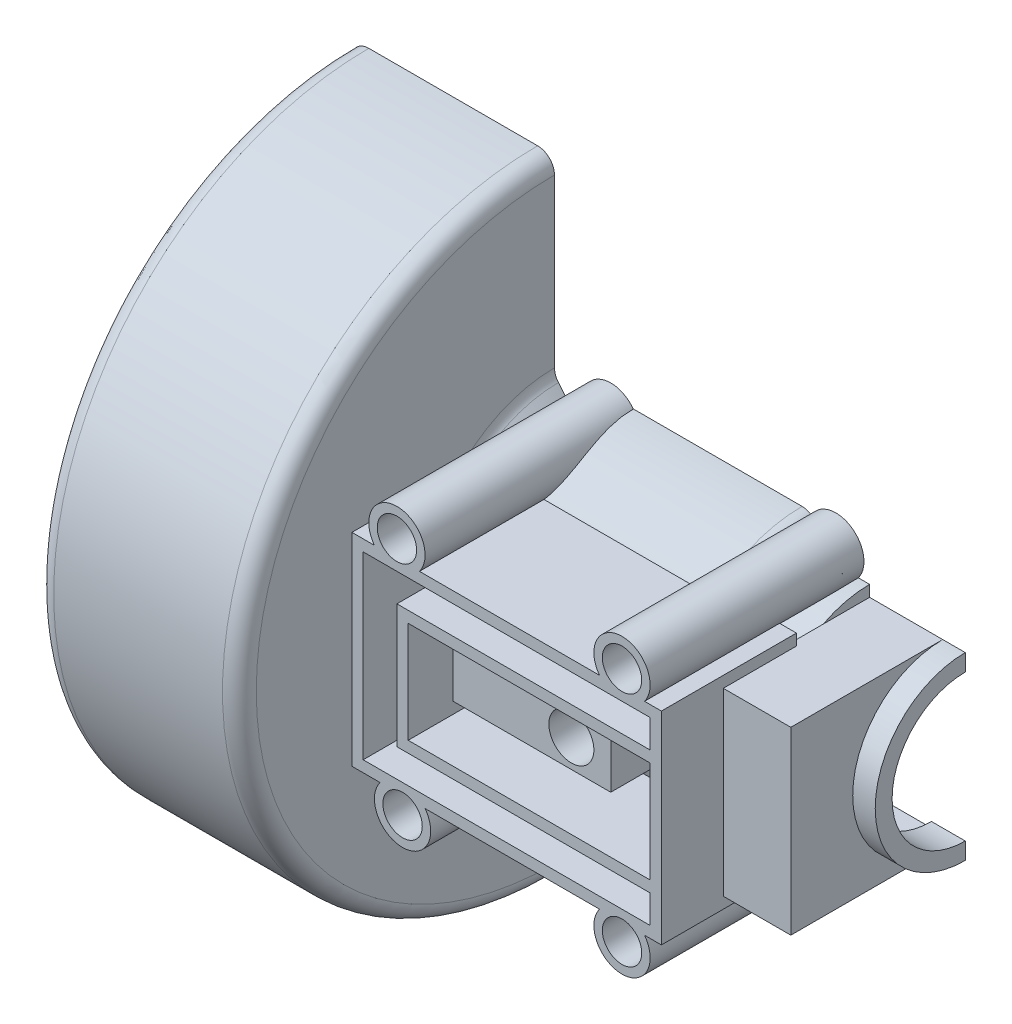
SolidWorks part; units mm, degrees
ref_plane "Plan1" through (0, 0, 0) normal (0, 0, 1) x (1, 0, 0)
ref_plane "Plan2" through (0, 0, 0) normal (0, 1, 0) x (1, 0, 0)
ref_plane "Plan3" through (0, 0, 0) normal (1, 0, 0) x (0, 0, -1)
sketch "Esquisse1" plane through (0, 0, 0) normal (0, 0, 1) x (1, 0, 0)
  line L0 (-80, 0) -> (140, 0) construction
  line L1 (55, 22) -> (85, 22)
  line L2 (4, 16) -> (4, 53)
  line L3 (7, 56) -> (37, 56)
  line L4 (40, 53) -> (40, 23.3262)
  line L5 (40.6953, 21.4056) -> (42.53, 19.2041)
  line L6 (55, 16) -> (55, 22)
  line L7 (46.75, 18.8156) -> (52.167, 23.309)
  line L8 (54.0823, 24) -> (84, 24)
  line L9 (38.6953, 20.6815) -> (44, 14.3159)
  line L10 (38, 51) -> (38, 22.6021)
  line L11 (9, 54) -> (35, 54)
  line L12 (6, 13) -> (6, 51)
  line L13 (1.5, 13) -> (3, 13)
  line L14 (1.5, 15) -> (3, 15)
  line L15 (4.5, 13) -> (6, 13)
  line L16 (1.5, 13) -> (1.5, 15)
  line L18 (44, 14.3159) -> (44, 14)
  line L19 (44, 14) -> (46, 14)
  line L20 (46, 14) -> (46, 16)
  line L21 (46, 16) -> (55, 16)
  line L22 (85, 22) -> (85, 16)
  line L23 (85, 16) -> (94, 16)
  line L24 (94, 16) -> (94, 14)
  line L25 (94, 14) -> (96, 14)
  line L26 (96, 14) -> (96, 18)
  line L28 (87, 21) -> (87, 20)
  line L29 (89, 18) -> (96, 18)
  arc A0 (4.5, 13) -> (3, 13) centre (3.75, 13) ccw
  arc A1 (4, 16) -> (3, 15) centre (3, 16) cw
  arc A2 (7, 56) -> (4, 53) centre (7, 53) ccw
  arc A3 (9, 54) -> (6, 51) centre (9, 51) ccw
  arc A4 (40, 53) -> (37, 56) centre (37, 53) ccw
  arc A5 (38, 51) -> (35, 54) centre (35, 51) ccw
  arc A6 (38.6953, 20.6815) -> (38, 22.6021) centre (41, 22.6021) cw
  arc A7 (40.6953, 21.4056) -> (40, 23.3262) centre (43, 23.3262) cw
  arc A8 (46.75, 18.8156) -> (42.53, 19.2041) centre (44.8346, 21.1246) cw
  arc A9 (54.0823, 24) -> (52.167, 23.309) centre (54.0823, 21) ccw
  arc A10 (87, 21) -> (84, 24) centre (84, 21) ccw
  arc A13 (89, 18) -> (87, 20) centre (89, 20) cw
  point P31 (4, 15)
  point P37 (4, 56)
  point P42 (40, 56)
  point P57 (55, 22)
  point P60 (85, 22)
  dimension "D7" = 1.5
  dimension "D14" = 1
  dimension "D15" = 3
  dimension "D16" = 9
  dimension "D1" = 56
  dimension "D2" = 2
  dimension "D3" = 36
  dimension "D4" = 13
  dimension "D5" = 2
  dimension "D6" = 2.5
  dimension "D8" = 14
  dimension "D9" = 16
  dimension "D10" = 9
  dimension "D11" = 2
  dimension "D12" = 38
  dimension "D13" = 30
  dimension "D17" = 22
  dimension "D18" = 16
revolve "Base-Révolution" add sketch "Esquisse1" angle 180 about L0
sketch "Esquisse2" plane through (96, 0, 0) normal (1, 0, 0) x (0, 0, -1)
  line L0 (0, 23.3262) -> (0, 53) construction
  line L1 (0, 16) -> (-27, 16)
  line L2 (0, 16) -> (0, 14)
  line L3 (0, -16) -> (-27, -16)
  line L4 (-27, 16) -> (-27, -16)
  line L5 (0, 14) -> (-25, 14)
  line L6 (-25, 14) -> (-25, -14)
  line L7 (0, -14) -> (-25, -14)
  line L8 (0, -14) -> (0, -16)
  dimension "D1" = 16
  dimension "D2" = 32
  dimension "D3" = 27
  dimension "D4" = 2
extrude "Boss.-Extru.1" add sketch "Esquisse2" along normal blind 11
sketch "Esquisse3" plane through (96, 0, 0) normal (1, 0, 0) x (0, 0, -1)
  line L1 (-25, 14) -> (-4, 14)
  line L2 (-25, 14) -> (-25, 6)
  line L3 (-25, -14) -> (-4, -14)
  line L4 (-25, -6) -> (-25, -14)
  line L5 (-25, 6) -> (-16.9706, 6)
  line L7 (-25, -6) -> (-16.9706, -6)
  line L8 (-16.9706, 6) -> (-16.9706, -6)
  arc A0 (-4, 14) -> (-4, -14) centre (0, 0) ccw
  arc A1 (-11.3137, 14) -> (-11.3137, -14) centre (0, 0) ccw construction
  dimension "D1" = 6
  dimension "D2" = 12
extrude "Boss.-Extru.5" add sketch "Esquisse3" along normal blind 1
sketch "Esquisse4" plane through (107, 0, 0) normal (1, 0, 0) x (0, 0, -1)
  line L0 (-27, -16) -> (0, -16)
  line L1 (-27, 16) -> (0, 16)
  line L2 (-27, 16) -> (-27, -16)
  line L3 (0, -16) -> (0, -13)
  line L4 (0, 16) -> (0, 13)
  arc A0 (0, 13) -> (0, -13) centre (0, 0) ccw
  dimension "D1" = 13
extrude "Boss.-Extru.6" add sketch "Esquisse4" along normal blind 2
ref_plane "Plan4" through (0, 0, 38) normal (0, 0, 1) x (1, 0, 0)
sketch "Esquisse5" plane through (0, 0, 38) normal (0, 0, 1) x (1, 0, 0)
  line L0 (40, -53) -> (40, 53) construction
  line L1 (97, 18) -> (42, 18)
  line L2 (97, 18) -> (97, -18)
  line L3 (97, -18) -> (42, -18)
  line L4 (42, 18) -> (42, -18)
  line L5 (95, 16) -> (44, 16)
  line L6 (44, 16) -> (44, -16)
  line L7 (95, -16) -> (44, -16)
  line L8 (95, 16) -> (95, 11)
  line L9 (95, 9) -> (95, -9)
  line L10 (95, 11) -> (50, 11)
  line L12 (95, -11) -> (50, -11)
  line L13 (50, 11) -> (50, -11)
  line L14 (95, -9) -> (52, -9)
  line L15 (52, 9) -> (52, -9)
  line L16 (95, 9) -> (52, 9)
  line L17 (95, -11) -> (95, -16)
  dimension "D1" = 55
  dimension "D2" = 2
  dimension "D3" = 36
  dimension "D4" = 18
  dimension "D6" = 45
  dimension "D7" = 22
  dimension "D8" = 11
  dimension "D5" = 2
  dimension "D9" = 2
extrude "Boss.-Extru.7" add sketch "Esquisse5" against normal blind 24
sketch "Esquisse6" plane through (0, 0, 38) normal (0, 0, 1) x (1, 0, 0)
  line L0 (40, -53) -> (40, 53) construction
  circle A0 centre (90, 21) radius 5
  circle A1 centre (50, 21) radius 5
  circle A2 centre (90, -21) radius 5
  circle A3 centre (51, -21) radius 5
  dimension "D1" = 10
  dimension "D2" = 50
  dimension "D3" = 21
  dimension "D4" = 10
  dimension "D5" = 40
  dimension "D6" = 10
  dimension "D7" = 42
  dimension "D8" = 10
  dimension "D9" = 42
  dimension "D10" = 21
extrude "Boss.-Extru.8" add sketch "Esquisse6" against normal blind 38
sketch "Esquisse7" plane through (0, 0, 38) normal (0, 0, 1) x (1, 0, 0)
  circle A0 centre (90, 21) radius 3.5
  circle A1 centre (50, 21) radius 3.5
  circle A2 centre (51, -21) radius 3.5
  circle A3 centre (90, -21) radius 3.5
  dimension "D1" = 7
  dimension "D2" = 7
  dimension "D3" = 7
  dimension "D4" = 7
extrude "Enlèv. mat.-Extru.1" cut sketch "Esquisse7" against normal through all
sketch "Esquisse8" plane through (0, 0, 0) normal (0, 0, 1) x (1, 0, 0)
  line L0 (40, -53) -> (40, 53) construction
  line L1 (54, 5) -> (82, 5)
  line L2 (54, 5) -> (54, -5)
  line L3 (54, -5) -> (82, -5)
  line L4 (82, 5) -> (82, -5)
  dimension "D1" = 28
  dimension "D2" = 14
  dimension "D3" = 10
  dimension "D4" = 5
extrude "Enlèv. mat.-Extru.5" cut sketch "Esquisse8" along normal blind 22
sketch "Esquisse9" plane through (0, 0, 22) normal (0, 0, -1) x (-1, 0, 0)
  line L1 (-82, 5) -> (-54, 5)
  line L2 (-82, 5) -> (-82, -5)
  line L3 (-82, -5) -> (-54, -5)
  line L4 (-54, 5) -> (-54, -5)
extrude "Boss.-Extru.11" add sketch "Esquisse9" against normal blind 10
sketch "Esquisse10" plane through (0, 0, 32) normal (0, 0, 1) x (1, 0, 0)
  line L2 (97, 0) -> (96, 0) construction
  line L3 (40, -53) -> (40, 53) construction
  circle A1 centre (75, 0) radius 4
  dimension "D1" = 8
  dimension "D2" = 35
extrude "Enlèv. mat.-Extru.6" cut sketch "Esquisse10" against normal through all
sketch "Esquisse11" plane through (55, 0, 0) normal (1, 0, 0) x (0, 0, -1)
  circle A0 centre (0, 0) radius 22
  dimension "D1" = 44
extrude "Enlèv. mat.-Extru.7" cut sketch "Esquisse11" along normal blind 30
sketch "Esquisse12" plane through (55, 0, 0) normal (1, 0, 0) x (0, 0, -1)
  circle A0 centre (0, 0) radius 16
  dimension "D1" = 32
extrude "Enlèv. mat.-Extru.8" cut sketch "Esquisse12" against normal blind 8
sketch "Esquisse13" plane through (109, 0, 0) normal (1, 0, 0) x (0, 0, -1)
  line L0 (0, 16) -> (0, -16)
  arc A0 (0, 16) -> (0, -16) centre (0, 0) ccw
  dimension "D1" = 32
extrude "Boss.-Extru.12" add sketch "Esquisse13" along normal blind 4
sketch "Esquisse14" plane through (113, 0, 0) normal (1, 0, 0) x (0, 0, -1)
  circle A0 centre (0, 0) radius 13
  dimension "D1" = 26
extrude "Enlèv. mat.-Extru.9" cut sketch "Esquisse14" against normal blind 10
sketch "Esquisse15" plane through (0, 0, 0) normal (0, 1, 0) x (1, 0, 0)
  line L1 (0, 0) -> (121, 0)
  line L2 (0, 0) -> (0, -65)
  line L3 (0, -65) -> (121, -65)
  line L4 (121, 0) -> (121, -65)
extrude "demi coupe " [suppressed] cut sketch "Esquisse15" along normal through all
